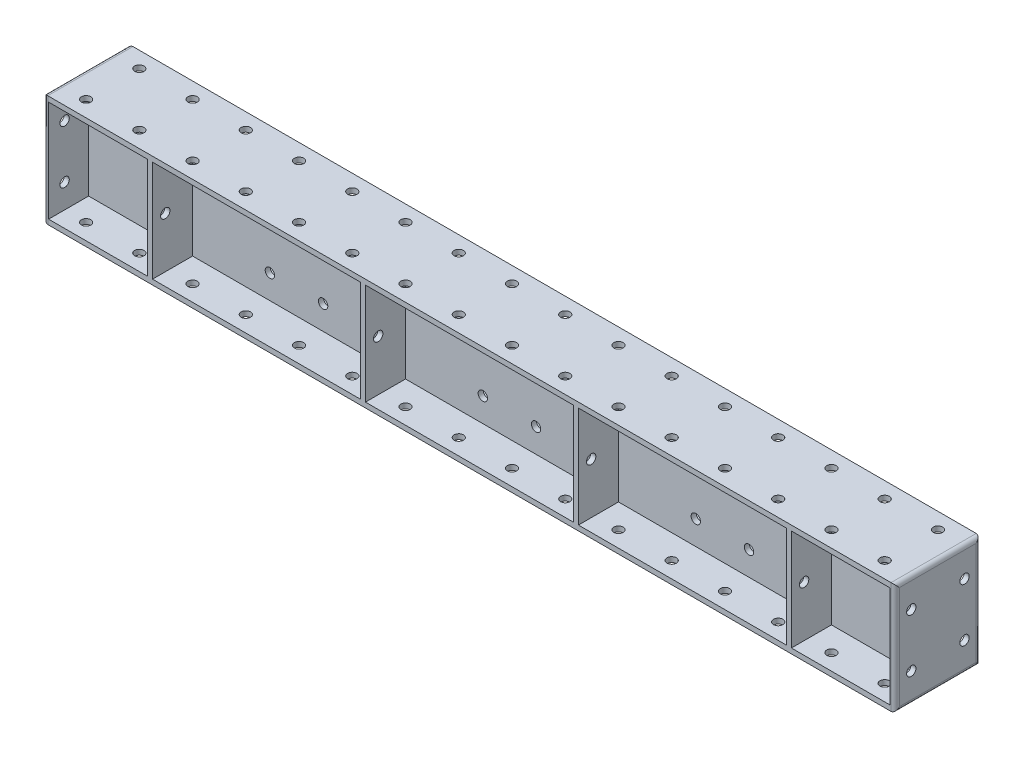
SolidWorks part; units mm, degrees
ref_plane "前视基准面" through (0, 0, 0) normal (0, 0, 1) x (1, 0, 0)
ref_plane "上视基准面" through (0, 0, 0) normal (0, 1, 0) x (1, 0, 0)
ref_plane "右视基准面" through (0, 0, 0) normal (1, 0, 0) x (0, 0, -1)
sketch "草图1" plane through (0, 0, 0) normal (0, 0, 1) x (1, 0, 0)
  line L1 (0, 0) -> (2000, 0)
  line L2 (0, 0) -> (0, 262)
  line L3 (0, 262) -> (2000, 262)
  line L4 (2000, 0) -> (2000, 262)
  dimension "D1" = 2000
  dimension "D2" = 262
extrude "拉伸1" add sketch "草图1" along normal blind 200
sketch "草图5" plane through (0, 0, 200) normal (0, 0, 1) x (1, 0, 0)
  line L0 (2000, 262) -> (0, 262) construction
  line L1 (12, 250) -> (244, 250)
  line L2 (12, 250) -> (12, 12)
  line L3 (12, 12) -> (244, 12)
  line L4 (244, 250) -> (244, 12)
  line L5 (0, 0) -> (2000, 0) construction
  line L6 (0, 262) -> (0, 0) construction
  line L8 (256, 250) -> (744, 250)
  line L9 (256, 250) -> (256, 12)
  line L10 (256, 12) -> (744, 12)
  line L11 (744, 250) -> (744, 12)
  line L12 (756, 250) -> (1244, 250)
  line L13 (756, 250) -> (756, 12)
  line L14 (756, 12) -> (1244, 12)
  line L15 (1244, 250) -> (1244, 12)
  line L16 (1256, 250) -> (1744, 250)
  line L17 (1256, 250) -> (1256, 12)
  line L18 (1256, 12) -> (1744, 12)
  line L19 (1744, 250) -> (1744, 12)
  line L32 (1756, 250) -> (1988, 250)
  line L33 (1756, 250) -> (1756, 12)
  line L34 (1756, 12) -> (1988, 12)
  line L35 (1988, 250) -> (1988, 12)
  dimension "D1" = 12
  dimension "D2" = 12
  dimension "D3" = 12
  dimension "D4" = 232
  dimension "D5" = 12
  dimension "D6" = 488
  dimension "D7" = 488
  dimension "D8" = 12
  dimension "D9" = 488
  dimension "D10" = 12
  dimension "D11" = 12
  dimension "D17" = 232
extrude "拉伸10" cut sketch "草图5" against normal through all
sketch "草图7" plane through (0, 0, 0) normal (0, -1, 0) x (1, 0, 0)
  line L0 (0, 100) -> (3607.9066, 100) construction
  line L1 (0, 200) -> (0, 0) construction
  line L2 (2000, 200) -> (2000, 0) construction
  line L3 (0, 106) -> (2000, 106)
  line L4 (0, 106) -> (0, 94)
  line L5 (0, 94) -> (2000, 94)
  line L6 (2000, 106) -> (2000, 94)
  dimension "D1" = 6
  dimension "D2" = 6
extrude "拉伸13" add sketch "草图7" against normal blind 260
sketch "草图8" plane through (0, 0, 0) normal (0, -1, 0) x (1, 0, 0)
  line L0 (0, 0) -> (2000, 0) construction
  line L1 (0, 200) -> (0, 0) construction
  circle A0 centre (62.5, 37.5) radius 11
  dimension "D1" = 37.5
  dimension "D3" = 22
  dimension "D2" = 62.5
extrude "拉伸14" cut sketch "草图8" against normal through all
pattern_linear "阵列(线性)3" count 16 spacing 125 along (1, 0, 0) count 2 spacing 125 along (0, 0, 1) of "拉伸14"
sketch "草图10" plane through (0, 0, 0) normal (-1, 0, 0) x (0, 0, 1)
  line L0 (200, 0) -> (0, 0) construction
  line L1 (0, 262) -> (0, 0) construction
  circle A0 centre (37.5, 68.5) radius 11
  dimension "D1" = 68.5
  dimension "D3" = 22
  dimension "D2" = 37.5
extrude "拉伸16" cut sketch "草图10" against normal blind 20
pattern_linear "阵列(线性)5" count 2 spacing 125 along (0, 0, 1) count 2 spacing 125 along (0, 1, 0) of "拉伸16"
sketch "草图11" plane through (2000, 0, 0) normal (1, 0, 0) x (0, 0, -1)
  line L0 (-200, 0) -> (0, 0) construction
  line L1 (-200, 0) -> (-200, 262) construction
  circle A0 centre (-162.5, 68.5) radius 11
  dimension "D1" = 68.5
  dimension "D3" = 22
  dimension "D2" = 37.5
extrude "拉伸17" cut sketch "草图11" against normal blind 20
pattern_linear "阵列(线性)6" count 2 spacing 125 along (0, 0, -1) count 2 spacing 125 along (0, 1, 0) of "拉伸17"
sketch "草图12" plane through (1756, 0, 0) normal (1, 0, 0) x (0, 0, -1)
  line L0 (-200, 250) -> (-200, 12) construction
  line L1 (-106, 12) -> (-200, 12) construction
  circle A0 centre (-170.1213, 131) radius 11
  dimension "D1" = 29.8787
  dimension "D3" = 22
  dimension "D2" = 119
extrude "拉伸18" cut sketch "草图12" against normal blind 1550
pattern_linear "阵列(线性)8" count 2 spacing 140.2427 along (0, 0, -1) of "拉伸18"
fillet "圆角1" radius 10 4 edges at (0, 0, 100) (0, 131, 0) (0, 131, 200) (0, 262, 100)
fillet "圆角2" radius 10 4 edges at (2000, 262, 100) (2000, 131, 0) (2000, 0, 100) (2000, 131, 200)
sketch "草图13" plane through (0, 0, 106) normal (0, 0, 1) x (1, 0, 0)
  line L0 (-256, 131) -> (49744, 131) construction
  line L2 (744, 250) -> (744, 12) construction
  line L4 (500, -750) -> (500, 49250) construction
  line L6 (744, 250) -> (256, 250) construction
  circle A0 centre (437.5, 68.5) radius 11
  point P5 (744, 131)
  point P10 (500, 250)
  dimension "D1" = 62.5
  dimension "D3" = 22
  dimension "D2" = 62.5
extrude "拉伸19" cut sketch "草图13" against normal through all
pattern_linear "阵列(线性)9" count 2 spacing 125 along (1, 0, 0) count 2 spacing 125 along (0, 1, 0) of "拉伸19"
pattern_linear "阵列(线性)10" count 3 spacing 500 along (1, 0, 0) of "拉伸19", "阵列(线性)9"
